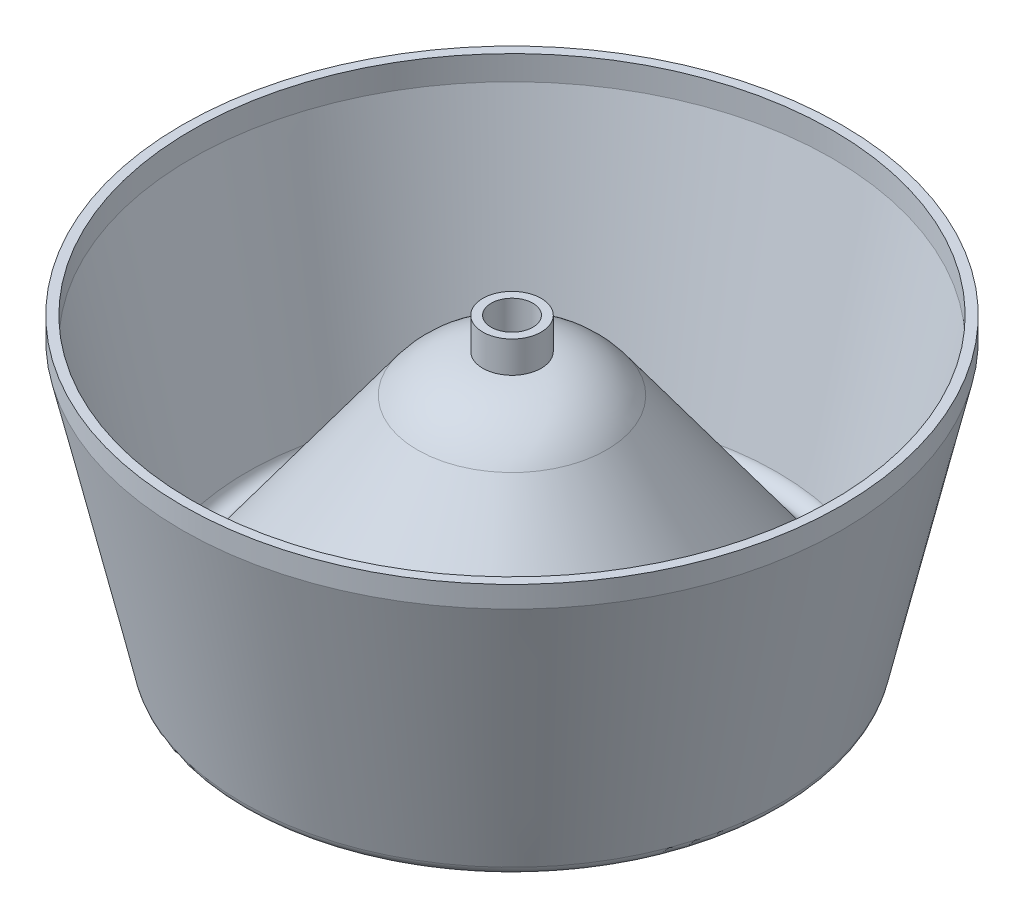
SolidWorks part; units mm, degrees
ref_plane "Front Plane" through (0, 0, 0) normal (0, 0, 1) x (1, 0, 0)
ref_plane "Top Plane" through (0, 0, 0) normal (0, 1, 0) x (1, 0, 0)
ref_plane "Right Plane" through (0, 0, 0) normal (1, 0, 0) x (0, 0, -1)
sketch "Sketch1" plane through (0, 0, 0) normal (1, 0, 0) x (0, 0, -1)
  line L5 (-80.2272, 37.7431) -> (80.2272, 37.7431) construction
  line L6 (-80.2272, 37.7431) -> (-80.2272, -37.7431) construction
  line L7 (-80.2272, -37.7431) -> (80.2272, -37.7431) construction
  line L8 (80.2272, 37.7431) -> (80.2272, -37.7431) construction
  line L9 (-80.2272, 37.7431) -> (80.2272, -37.7431) construction
  line L10 (-80.2272, -37.7431) -> (80.2272, 37.7431) construction
  line L16 (-59.1486, -32.4047) -> (-21.0684, 19.9267)
  line L19 (0, 0) -> (0, -37.7431) construction
  line L31 (-79.0589, 32.6139) -> (-64.4995, -31.3058)
  line L37 (-76.8419, 31.8859) -> (-63.5269, -26.5702)
  line L38 (-58.1761, -27.6691) -> (-22.6855, 21.1035)
  line L39 (-7, 30.2081) -> (-7, 37.7431)
  line L40 (-7, 37.7431) -> (-5, 37.7431)
  line L42 (-5, 28.3387) -> (-5, 37.7431)
  line L44 (-78.2772, 38.1872) -> (-62.5494, -30.8617) construction
  line L45 (-60.7658, -31.228) -> (-22.6855, 21.1035) construction
  line L46 (-79.0589, 32.6139) -> (-79.0589, 37.7431)
  line L47 (-79.0589, 37.7431) -> (-76.8419, 37.7431)
  line L48 (-76.8419, 37.7431) -> (-76.8419, 31.8859)
  line L49 (-80.2272, 37.7431) -> (-64.4995, -31.3058) construction
  arc A7 (-59.1486, -32.4047) -> (-64.4995, -31.3058) centre (-61.5744, -30.6396) cw
  arc A9 (-22.6855, 21.1035) -> (-7, 30.2081) centre (-4.5333, 7.8946) cw
  arc A10 (-21.0684, 19.9267) -> (-5, 28.3387) centre (-4.5333, 7.8946) cw
  arc A11 (-58.1761, -27.6691) -> (-63.5269, -26.5702) centre (-60.6018, -25.9039) cw
  arc A12 (-60.7658, -31.228) -> (-62.5494, -30.8617) centre (-61.5744, -30.6396) cw construction
  point P0 (0, 0)
  point P14 (17.18, -37.7431)
  point P29 (-63.0332, -37.7431)
  dimension "D1" = 2
  dimension "D3" = 3
  dimension "D2" = 3
revolve "Revolve7" add sketch "Sketch1" angle 360 about L19
ref_plane "Plane1" through (0, 18.0987, -24.872) normal (0, 0.5884, -0.8086) x (-1, 0, 0)
sketch "Sketch2" plane through (0, 18.0987, -24.872) normal (0, 0.5884, -0.8086) x (-1, 0, 0)
  line L0 (0, 0) -> (0, -58.519) construction
  line L1 (-7.5, 0) -> (7.5, 0)
  line L2 (7.5, 0) -> (7.5, -40)
  line L4 (-7.5, 0) -> (-7.5, -40)
  line L5 (-7.5, -40) -> (7.5, -40)
  point P6 (0, 0)
